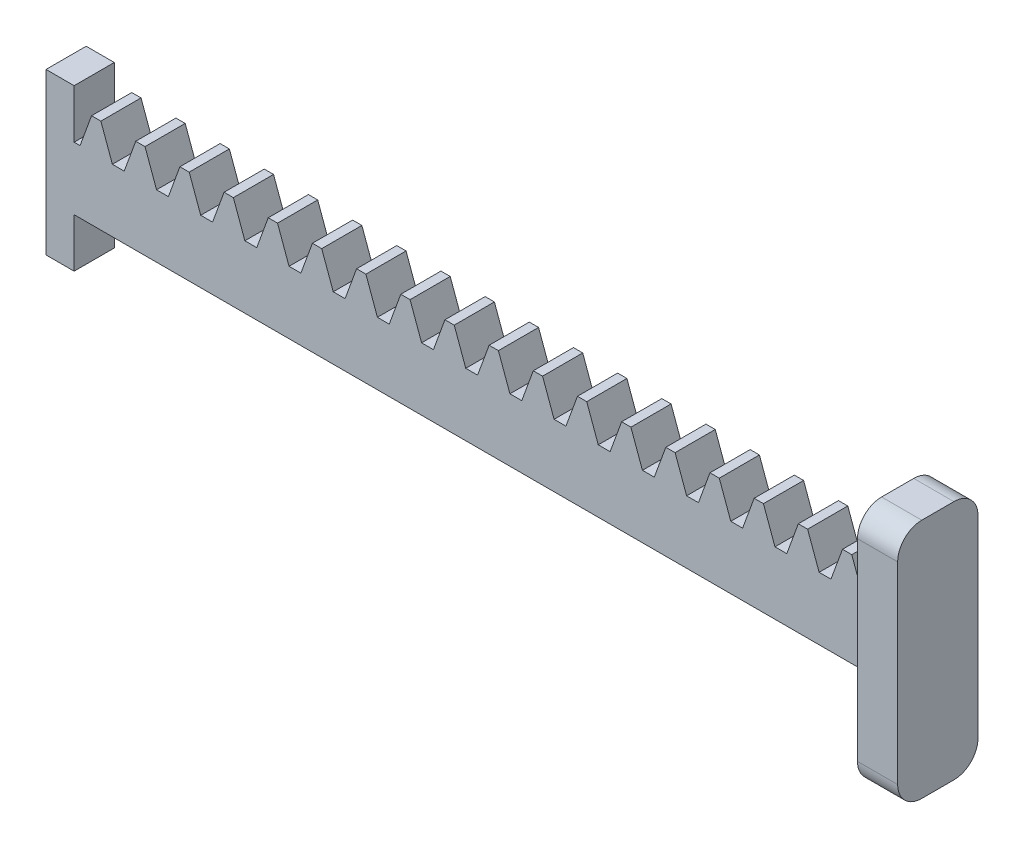
SolidWorks part; units mm, degrees
extrude "Blank" add sketch "BlankSke" against normal blind 5
sketch "BlankSke" plane through (0, 0, 0) normal (0, 0, 1) x (1, 0, 0)
  line L1 (0, 0) -> (100, 0)
  line L2 (0, 0) -> (0, 11.75)
  line L3 (0, 11.75) -> (100, 11.75)
  line L4 (100, 0) -> (100, 11.75)
  dimension "Length" = 100
  dimension "Blank_height" = 11.75
ref_plane "Plane1" through (0, 0, 0) normal (0, 0, 1) x (1, 0, 0)
ref_plane "Plane2" through (0, 0, 0) normal (0, 1, 0) x (1, 0, 0)
ref_plane "Plane3" through (0, 0, 0) normal (1, 0, 0) x (0, 0, -1)
other "Configuration Table"
sketch "HoldingSke" plane through (0, 0, 0) normal (0, 1, 0) x (1, 0, 0)
  line L0 (0, 0) -> (0.0795, 0.5659)
  line L1 (-15, 0) -> (100, 0) construction
  line L2 (0, 0) -> (-2.1039, 2.3779)
  line L3 (0, 0) -> (-11.863, 4.5341)
  line L4 (0, 0) -> (8.1152, 2.9537)
  line L5 (0, 0) -> (-23.7986, -8.8762)
  line L6 (0, 0) -> (-10.5278, -7.1032)
  line L9 (-71.009, 38.7566) -> (22.9603, 72.9586)
  line L10 (-76.2, 4.1279) -> (-66.2, 4.1279)
  line L11 (0, 0) -> (-5, 0)
  line L12 (-76.2, 101.6) -> (-76.147, 101.6)
  line L13 (24.9733, 27.94) -> (52.9518, 28.4284)
  line L14 (24.9733, 27.94) -> (24.9743, 27.94)
  line L15 (24.9733, 27.94) -> (100.4006, 29.5858)
  circle A0 centre (0, 0) radius 19.05
  circle A1 centre (0, 0) radius 5
  circle A2 centre (0, 0) radius 12.7
  dimension "MPH" = 10
  dimension "Diameter" = 38.1
  dimension "Num_teeth" = 20
  dimension "Pitch" = 0.5714
  dimension "Show_teeth" = 998
  dimension "Thickness" = 12.7
  dimension "Ap" = 20
  dimension "Pitch_height" = 10
  dimension "Width" = 5
  dimension "Backlash" = 0.053
  dimension "Addendum_fac" = 1
  dimension "Dedendum_fac" = 1.25
  dimension "Clearance_fac" = 0.25
  dimension "Dedendum_add" = 0.001
  dimension "Length" = 100
  dimension "Module" = 1.75
sketch "TooCutSkeIll" plane through (0, 0, 0) normal (0, 0, 1) x (1, 0, 0)
  line L0 (-2.1536, 11.7039) -> (-0.8423, 8.101)
  line L1 (-0.4302, 7.8125) -> (0.4302, 7.8125)
  line L2 (0.8423, 8.101) -> (2.1536, 11.7039)
  line L3 (100, 11.75) -> (0, 11.75) construction
  line L4 (0, 0) -> (0, 64.897) construction
  line L5 (-13.208, 10) -> (12.954, 10) construction
  line L6 (0, 0) -> (100, 0) construction
  line L7 (1.5334, 10) -> (1.5334, 48.7463) construction
  line L8 (-1.5334, 10) -> (-1.5334, 48.7463) construction
  line L9 (2.2194, 11.75) -> (2.2194, 11.7754)
  line L10 (-2.2194, 11.75) -> (-2.2194, 11.7754)
  line L11 (-2.2194, 11.7754) -> (2.2194, 11.7754)
  arc A0 (0.4302, 7.8125) -> (0.8423, 8.101) centre (0.4302, 8.251) ccw
  arc A1 (-0.8423, 8.101) -> (-0.4302, 7.8125) centre (-0.4302, 8.251) ccw
  arc A2 (2.2194, 11.75) -> (2.1536, 11.7039) centre (2.2194, 11.68) ccw
  arc A3 (-2.1536, 11.7039) -> (-2.2194, 11.75) centre (-2.2194, 11.68) ccw
  dimension "Pitch_height" = 10
  dimension "Addendum_plus" = 1.7754
  dimension "Pressure_angle" = 20
  dimension "Gap_width" = 3.0669
  dimension "Dedendum" = 2.1875
extrude "ToothCutIll" [suppressed] cut sketch "TooCutSkeIll" against normal through all
sketch "TooCutSkeSim" plane through (0, 0, 0) normal (0, 0, 1) x (1, 0, 0)
  line L0 (0.7373, 7.8125) -> (-0.7373, 7.8125)
  line L1 (2.1796, 11.7754) -> (0.7373, 7.8125)
  line L2 (0, 17.4625) -> (0, 53.467) construction
  line L3 (2.1796, 11.7754) -> (-2.1796, 11.7754)
  line L6 (-2.1796, 11.7754) -> (-0.7373, 7.8125)
  line L9 (-1.5334, 10) -> (1.5334, 10) construction
  line L10 (0, 0) -> (100, 0) construction
  line L11 (1.5334, 10) -> (1.5334, 53.467) construction
  line L12 (-1.5334, 10) -> (-1.5334, 53.467) construction
  dimension "Pitch_height" = 10
  dimension "Addendum_plus" = 1.7754
  dimension "Pressure_angle" = 20
  dimension "Gap_width" = 3.0669
  dimension "Dedendum" = 2.1875
extrude "ToothCutSim" cut sketch "TooCutSkeSim" against normal through all
pattern_linear "TeethCuts" count 19 spacing 5.4978 along (1, 0, 0) of "ToothCutIll", "ToothCutSim"
sketch "Esquisse1" plane through (0, 0, -5) normal (0, 0, -1) x (-1, 0, 0)
  line L0 (0, 7.8125) -> (0, 0) construction
  line L1 (0, 13.9062) -> (0, -6.0937)
  line L2 (0, 13.9062) -> (3.5, 13.9062)
  line L3 (3.5, 13.9062) -> (3.5, -6.0937)
  line L4 (3.5, -6.0937) -> (0, -6.0937)
  point P0 (0, 3.9062)
  point P6 (0, 3.9062)
  dimension "D1" = 20
  dimension "D2" = 3.5
extrude "Boss.-Extru.1" add sketch "Esquisse1" against normal through all
ref_plane "Plan1" through (0, 0, 45) normal (0, 0, -1) x (-1, 0, 0)
sketch "Esquisse4" plane through (100, 0, 0) normal (1, 0, 0) x (0, 0, -1)
  line L0 (0, 0) -> (0, 8.6438) construction
  line L1 (0.5, -10.6781) -> (4.5, -10.6781)
  line L2 (-2.5, -7.6781) -> (-2.5, 16.3219)
  line L3 (0.5, 19.3219) -> (4.5, 19.3219)
  line L4 (7.5, -7.6781) -> (7.5, 16.3219)
  line L5 (-2.5, -10.6781) -> (7.5, 19.3219) construction
  line L6 (-2.5, 19.3219) -> (7.5, -10.6781) construction
  arc A0 (4.5, -10.6781) -> (7.5, -7.6781) centre (4.5, -7.6781) ccw
  arc A1 (0.5, -10.6781) -> (-2.5, -7.6781) centre (0.5, -7.6781) cw
  arc A2 (4.5, 19.3219) -> (7.5, 16.3219) centre (4.5, 16.3219) cw
  arc A3 (-2.5, 16.3219) -> (0.5, 19.3219) centre (0.5, 16.3219) cw
  point P0 (2.5, 4.3219)
  dimension "D4" = 3
  dimension "D1" = 10
  dimension "D2" = 2.5
  dimension "D3" = 30
extrude "Boss.-Extru.2" add sketch "Esquisse4" along normal blind 5
equation "' \"Module@HoldingSke\" = 6.35"
equation "' \"Num_teeth@HoldingSke\" = 12"
equation "' \"Ap@HoldingSke\" =  20"
equation "' \"Ap@HoldingSke\" = 20"
equation "' \"Width@HoldingSke\" = 0.25 * 25.4"
equation "' \"Show_teeth@HoldingSke\" = 500"
equation "' \"Backlash@HoldingSke\" = 0.009 * 25.4"
equation "' \"Addendum_fac@HoldingSke\" = 1.0"
equation "' \"Dedendum_fac@HoldingSke\" = 1.25"
equation "' \"Dedendum_add@HoldingSke\" = 0.00005 * 25.4"
equation "' \"Clearance_fac@HoldingSke\" = 0.25"
equation "' \"Pitch_height@HoldingSke\" = 1 * 25.4"
equation "' \"Length@HoldingSke\" = 4.71 * 25.4"
equation "\"Pitch@HoldingSke\" = 1 / \"Module@HoldingSke\""
equation "\"MPH@HoldingSke\" = \"Dedendum_fac@HoldingSke\" / \"Pitch@HoldingSke\" + 2 * \"Dedendum_add@HoldingSke\" + 0.002 * 25.4"
equation "\"MPH@HoldingSke\" = ((sgn( \"MPH@HoldingSke\" - \"Pitch_height@HoldingSke\")+1)*( \"MPH@HoldingSke\" - \"Pitch_height@HoldingSke\"))/2 + \"Pitch_height@HoldingSke\""
equation "\"Blank_height@BlankSke\" = \"Pitch_height@HoldingSke\" + \"Addendum_fac@HoldingSke\"  / \"Pitch@HoldingSke\" "
equation "\"Length@BlankSke\" =  \"Length@HoldingSke\""
equation "\"Face_width@Blank\" = \"Width@HoldingSke\""
equation "\"Pressure_angle@TooCutSkeIll\" = \"Ap@HoldingSke\""
equation "\"Addendum_plus@TooCutSkeIll\" =  \"Addendum_fac@HoldingSke\"  / \"Pitch@HoldingSke\" + 0.001 *25.4"
equation "\"Dedendum@TooCutSkeIll\" = \"Dedendum_fac@HoldingSke\"  / \"Pitch@HoldingSke\""
equation "\"Pitch_height@TooCutSkeIll\" =  \"MPH@HoldingSke\""
equation "\"Gap_width@TooCutSkeIll\" = 3.14159265 / 2 / \"Pitch@HoldingSke\" + 6 * \"Backlash@HoldingSke\""
equation "\"Pressure_angle@TooCutSkeSim\" = \"Ap@HoldingSke\""
equation "\"Addendum_plus@TooCutSkeSim\" =  \"Addendum_fac@HoldingSke\"  / \"Pitch@HoldingSke\" + 0.001 * 25.4"
equation "\"Dedendum@TooCutSkeSim\" = \"Dedendum_fac@HoldingSke\"  / \"Pitch@HoldingSke\""
equation "\"Pitch_height@TooCutSkeSim\" =  \"MPH@HoldingSke\""
equation "\"Gap_width@TooCutSkeSim\" = 3.14159265 / 2 / \"Pitch@HoldingSke\" + 6 * \"Backlash@HoldingSke\""
equation "\"Root_fillet@TooCutSkeIll\" = \"Clearance_fac@HoldingSke\" / \"Pitch@HoldingSke\" + \"Dedendum_add@HoldingSke\""
equation "\"Break_rad@TooCutSkeIll\" = 0.02 / \"Pitch@HoldingSke\" * 2"
equation "\"Linear_pitch@TeethCuts\" = 3.14159265 / \"Pitch@HoldingSke\""
equation "\"Num_teeth@HoldingSke\" = int( ( \"Length@HoldingSke\" + 0 ) / (3.14159265 / \"Pitch@HoldingSke\")) + 0.9999  + 1"
equation " \"Num_teeth@TeethCuts\" = int( \"Show_teeth@HoldingSke\" ) + 1"
equation " \"Num_teeth@TeethCuts\" = ((sgn( \"Num_teeth@TeethCuts\" - \"Num_teeth@HoldingSke\" )-1)*( \"Num_teeth@TeethCuts\" - \"Num_teeth@HoldingSke\" ))/-2+ \"Num_teeth@HoldingSke\""
equation " \"Num_teeth@TeethCuts\" = ((sgn( \"Num_teeth@TeethCuts\" - 2.0)+1)*( \"Num_teeth@TeethCuts\" - 2.0))/2 +2.0"
